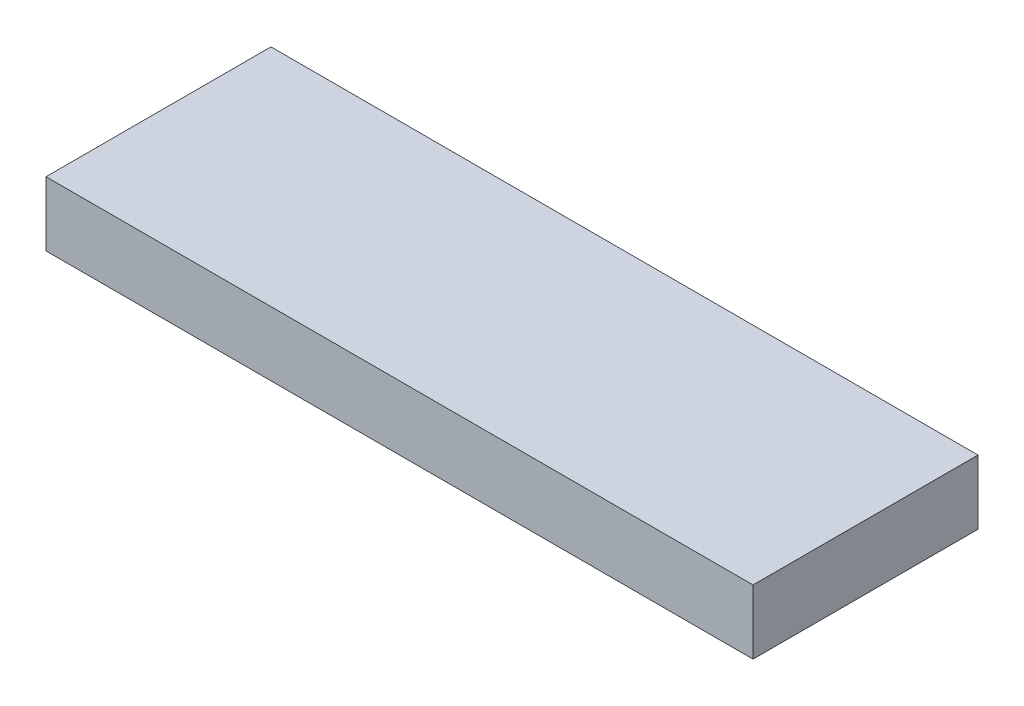
SolidWorks part; units mm, degrees
ref_plane "Front Plane" through (0, 0, 0) normal (0, 0, 1) x (1, 0, 0)
ref_plane "Top Plane" through (0, 0, 0) normal (0, 1, 0) x (1, 0, 0)
ref_plane "Right Plane" through (0, 0, 0) normal (1, 0, 0) x (0, 0, -1)
sketch "Sketch1" plane through (0, 0, 0) normal (0, 0, 1) x (1, 0, 0)
  line L1 (0, 0) -> (22, 0)
  line L2 (0, 0) -> (0, 2)
  line L3 (0, 2) -> (22, 2)
  line L4 (22, 0) -> (22, 2)
  dimension "D1" = 2
  dimension "D2" = 22
extrude "Boss-Extrude1" add sketch "Sketch1" along normal blind 7
